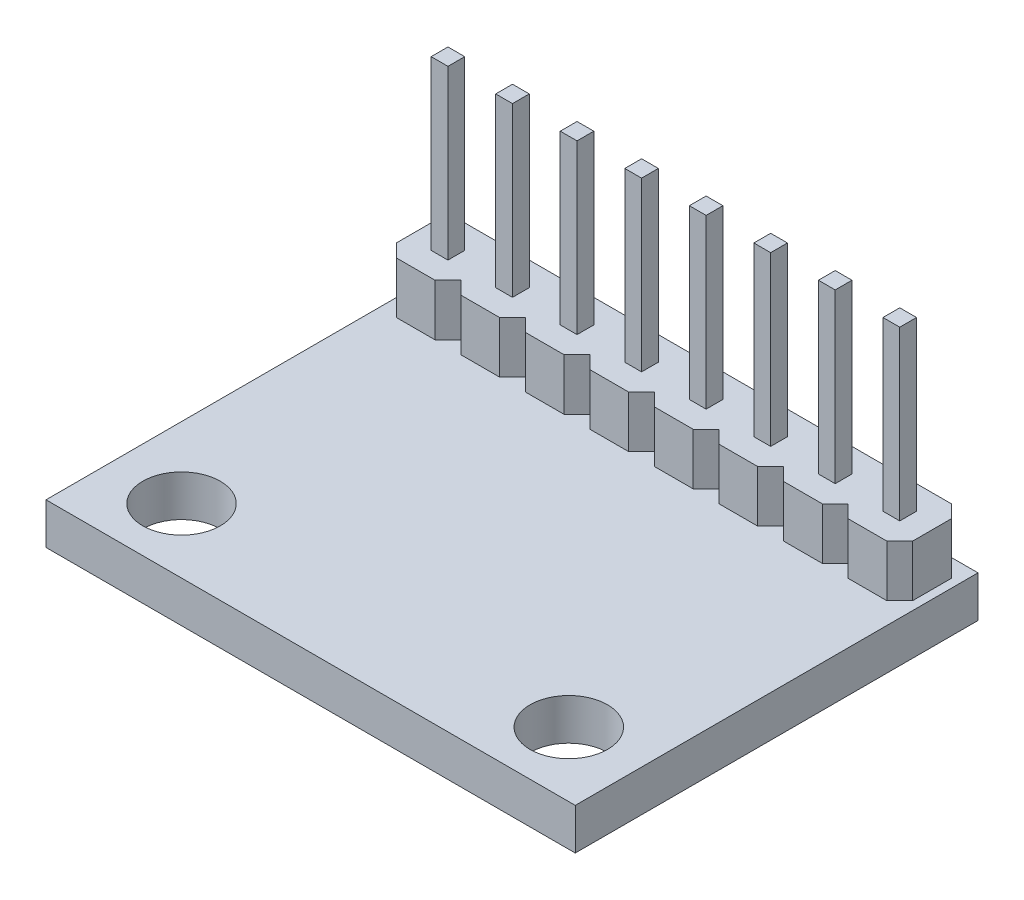
SolidWorks part; units mm, degrees
ref_plane "Front Plane" through (0, 0, 0) normal (0, 0, 1) x (1, 0, 0)
ref_plane "Top Plane" through (0, 0, 0) normal (0, 1, 0) x (1, 0, 0)
ref_plane "Right Plane" through (0, 0, 0) normal (1, 0, 0) x (0, 0, -1)
sketch "Sketch1" plane through (0, 0, 0) normal (0, 1, 0) x (1, 0, 0)
  line L0 (0, 0) -> (0, 42.7092) construction
  line L1 (0, 0) -> (50.0896, 0) construction
  line L3 (-10.25, 0) -> (10.25, 0)
  line L4 (-10.25, 0) -> (-10.25, 15.6)
  line L5 (-10.25, 15.6) -> (10.25, 15.6)
  line L6 (10.25, 0) -> (10.25, 15.6)
  circle A0 centre (7.5, 2.5) radius 1.5
  circle A1 centre (-7.5, 2.5) radius 1.5
  dimension "D3" = 3
  dimension "D1" = 15.6
  dimension "D2" = 20.5
  dimension "D4" = 15
  dimension "D5" = 2.5
extrude "Boss-Extrude1" add sketch "Sketch1" along normal blind 1.6 contours L5 L6 L3 L4
sketch "Sketch2" plane through (0, 1.6, 0) normal (0, 1, 0) x (1, 0, 0)
  line L0 (7.9187, 15.4) -> (7.4187, 14.9)
  line L1 (9.4187, 15.4) -> (7.9187, 15.4)
  line L2 (9.9187, 14.9) -> (9.9187, 13.4)
  line L3 (9.4187, 12.9) -> (7.9187, 12.9)
  line L4 (7.4187, 14.9) -> (7.4187, 13.4)
  line L5 (9.4187, 15.4) -> (9.9187, 14.9)
  line L6 (9.9187, 13.4) -> (9.4187, 12.9)
  line L7 (7.9187, 12.9) -> (7.4187, 13.4)
  line L8 (4.9187, 14.9) -> (4.9187, 13.4)
  line L9 (5.4187, 12.9) -> (4.9187, 13.4)
  line L10 (6.9187, 12.9) -> (5.4187, 12.9)
  line L11 (7.4187, 13.4) -> (6.9187, 12.9)
  line L12 (7.4187, 14.9) -> (7.4187, 13.4)
  line L13 (6.9187, 15.4) -> (7.4187, 14.9)
  line L14 (6.9187, 15.4) -> (5.4187, 15.4)
  line L15 (5.4187, 15.4) -> (4.9187, 14.9)
  line L16 (2.4187, 14.9) -> (2.4187, 13.4)
  line L17 (2.9187, 12.9) -> (2.4187, 13.4)
  line L18 (4.4187, 12.9) -> (2.9187, 12.9)
  line L19 (4.9187, 13.4) -> (4.4187, 12.9)
  line L20 (4.9187, 14.9) -> (4.9187, 13.4)
  line L21 (4.4187, 15.4) -> (4.9187, 14.9)
  line L22 (4.4187, 15.4) -> (2.9187, 15.4)
  line L23 (2.9187, 15.4) -> (2.4187, 14.9)
  line L24 (-0.0813, 14.9) -> (-0.0813, 13.4)
  line L25 (0.4187, 12.9) -> (-0.0813, 13.4)
  line L26 (1.9187, 12.9) -> (0.4187, 12.9)
  line L27 (2.4187, 13.4) -> (1.9187, 12.9)
  line L28 (2.4187, 14.9) -> (2.4187, 13.4)
  line L29 (1.9187, 15.4) -> (2.4187, 14.9)
  line L30 (1.9187, 15.4) -> (0.4187, 15.4)
  line L31 (0.4187, 15.4) -> (-0.0813, 14.9)
  line L32 (-2.5813, 14.9) -> (-2.5813, 13.4)
  line L33 (-2.0813, 12.9) -> (-2.5813, 13.4)
  line L34 (-0.5813, 12.9) -> (-2.0813, 12.9)
  line L35 (-0.0813, 13.4) -> (-0.5813, 12.9)
  line L36 (-0.0813, 14.9) -> (-0.0813, 13.4)
  line L37 (-0.5813, 15.4) -> (-0.0813, 14.9)
  line L38 (-0.5813, 15.4) -> (-2.0813, 15.4)
  line L39 (-2.0813, 15.4) -> (-2.5813, 14.9)
  line L40 (-5.0813, 14.9) -> (-5.0813, 13.4)
  line L41 (-4.5813, 12.9) -> (-5.0813, 13.4)
  line L42 (-3.0813, 12.9) -> (-4.5813, 12.9)
  line L43 (-2.5813, 13.4) -> (-3.0813, 12.9)
  line L44 (-2.5813, 14.9) -> (-2.5813, 13.4)
  line L45 (-3.0813, 15.4) -> (-2.5813, 14.9)
  line L46 (-3.0813, 15.4) -> (-4.5813, 15.4)
  line L47 (-4.5813, 15.4) -> (-5.0813, 14.9)
  line L48 (-7.5813, 14.9) -> (-7.5813, 13.4)
  line L49 (-7.0813, 12.9) -> (-7.5813, 13.4)
  line L50 (-5.5813, 12.9) -> (-7.0813, 12.9)
  line L51 (-5.0813, 13.4) -> (-5.5813, 12.9)
  line L52 (-5.0813, 14.9) -> (-5.0813, 13.4)
  line L53 (-5.5813, 15.4) -> (-5.0813, 14.9)
  line L54 (-5.5813, 15.4) -> (-7.0813, 15.4)
  line L55 (-7.0813, 15.4) -> (-7.5813, 14.9)
  line L56 (-10.0813, 14.9) -> (-10.0813, 13.4)
  line L57 (-9.5813, 12.9) -> (-10.0813, 13.4)
  line L58 (-8.0813, 12.9) -> (-9.5813, 12.9)
  line L59 (-7.5813, 13.4) -> (-8.0813, 12.9)
  line L60 (-7.5813, 14.9) -> (-7.5813, 13.4)
  line L61 (-8.0813, 15.4) -> (-7.5813, 14.9)
  line L62 (-8.0813, 15.4) -> (-9.5813, 15.4)
  line L63 (-9.5813, 15.4) -> (-10.0813, 14.9)
  line L64 (-9.9187, 15.4) -> (9.9187, 15.4) construction
  line L65 (0, 15.6) -> (0, 15.4) construction
  line L66 (10.25, 15.6) -> (-10.25, 15.6) construction
  point P0 (9.9187, 15.4)
  point P1 (7.4187, 12.9)
  point P2 (9.9187, 12.9)
  point P3 (7.4187, 15.4)
  dimension "D1" = 2.5
  dimension "D2" = 2.5
  dimension "D3" = 0.5
  dimension "D4" = 45
  dimension "D5" = 8
  dimension "D6" = 45
  dimension "D7" = 0.2
  dimension "D8" = 45
  dimension "D10" = 45
extrude "Boss-Extrude2" add sketch "Sketch2" along normal blind 2 contours L14 L15 L8 L9 L10 L11 L4 L13 | L22 L23 L16 L17 L18 L19 L8 L21 | L38 L39 L32 L33 L34 L35 L24 L37 | L30 L31 L24 L25 L26 L27 L16 L29 | L46 L47 L40 L41 L42 L43 L32 L45 | L54 L55 L48 L49 L50 L51 L40 L53 | L62 L63 L56 L57 L58 L59 L48 L61
sketch "Sketch3" plane through (0, 3.6, 0) normal (0, 1, 0) x (1, 0, 0)
  line L6 (8.6687, 15.4) -> (8.6687, 12.9) construction
  line L7 (8.3437, 13.825) -> (8.9937, 13.825)
  line L8 (8.3437, 13.825) -> (8.3437, 14.475)
  line L9 (8.3437, 14.475) -> (8.9937, 14.475)
  line L10 (8.9937, 13.825) -> (8.9937, 14.475)
  line L11 (8.3437, 13.825) -> (8.9937, 14.475) construction
  line L12 (8.3437, 14.475) -> (8.9937, 13.825) construction
  line L13 (9.4187, 15.4) -> (7.9187, 15.4) construction
  line L14 (9.4187, 12.9) -> (7.9187, 12.9) construction
  line L15 (9.9187, 14.15) -> (8.6687, 14.15) construction
  line L16 (9.9187, 14.9) -> (9.9187, 13.4) construction
  point P6 (8.6687, 14.15)
  dimension "D1" = 0.65
extrude "Boss-Extrude3" add sketch "Sketch3" along normal blind 6.5 and the other way blind 4
pattern_linear "LPattern1" count 8 spacing 2.5 along (-1, 0, 0) of "Boss-Extrude3"
